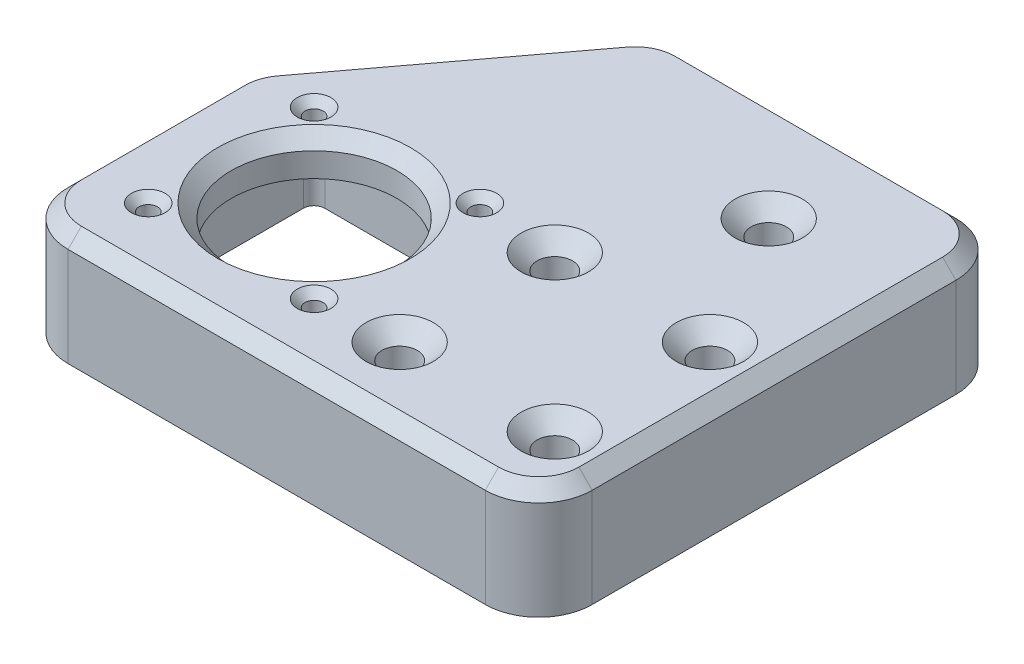
SolidWorks part; units mm, degrees
material "3.1355 (EN-AW 2024)"
ref_plane "Front" through (0, 0, 0) normal (0, 0, 1) x (1, 0, 0)
ref_plane "Top" through (0, 0, 0) normal (0, 1, 0) x (1, 0, 0)
ref_plane "Right" through (0, 0, 0) normal (1, 0, 0) x (0, 0, -1)
sketch "Эскиз1" plane through (0, 0, 0) normal (0, 1, 0) x (1, 0, 0)
  line L1 (-40, 40) -> (40, 40)
  line L2 (-40, 40) -> (-40, -40)
  line L3 (-40, -40) -> (40, -40)
  line L4 (40, 40) -> (40, -40)
  line L5 (-40, 40) -> (40, -40) construction
  line L6 (-40, -40) -> (40, 40) construction
  point P0 (0, 0)
  dimension "D1" = 80
extrude "База" add sketch "Эскиз1" along normal blind 21
sketch "Эскиз9" plane through (0, 21, 0) normal (0, 1, 0) x (1, 0, 0)
  line L6 (40, -40) -> (-40, -40)
  line L7 (-40, -40) -> (-40, 40)
  line L8 (-40, 40) -> (-93, 40)
  line L9 (-93, 40) -> (-93, -48)
  line L10 (-93, -48) -> (40, -48)
  line L11 (40, -48) -> (40, -40)
  dimension "D1" = 8
  dimension "D2" = 53
extrude "База-2" add sketch "Эскиз9" against normal up to surface (21 mm away) up to face at (0, 0, 0)
hole_wizard "Крепление-M6" positions "Эскиз6" profile "Эскиз8" countersink size "M6" standard "DIN" end condition through all
sketch "Эскиз6" plane through (0, 21, 0) normal (0, 1, 0) x (1, 0, 0)
  line L0 (0, 0) -> (-20, 0) construction
  line L1 (-20, 0) -> (-40, 0) construction
  line L5 (0, 0) -> (20, 0) construction
  line L6 (20, 0) -> (40, 0) construction
  line L10 (0, 0) -> (0, -20) construction
  line L11 (0, -20) -> (0, -40) construction
  line L15 (0, 0) -> (0, 20) construction
  line L16 (0, 20) -> (0, 40) construction
  line L20 (-34.5, -34.5) -> (-34.5, -20) construction
  line L21 (-34.5, -20) -> (-34.5, -5.5) construction
  line L26 (-34.5, -34.5) -> (-20, -34.5) construction
  line L27 (-20, -34.5) -> (-5.5, -34.5) construction
  point P0 (20, -20)
  point P2 (-20, 20)
  point P41 (-34.5, -5.5)
  point P43 (-5.5, -5.5)
  point P45 (-5.5, -34.5)
  point P47 (-34.5, -34.5)
  dimension "D1" = 29
  dimension "D2" = 20
sketch "Эскиз8" plane through (20, 21, 20) normal (1, 0, 0) x (0, 0, 1)
  line L0 (0, 0) -> (0, 21)
  line L1 (0, 21) -> (3.3, 21)
  line L2 (3.3, 21) -> (3.3, 3)
  line L3 (3.3, 3) -> (6.3, 0)
  line L5 (6.3, 0) -> (0, 0)
  line L6 (-3.3, 3) -> (-6.3, 0) construction
  line L11 (0, -6.35) -> (0, 107.95) construction
  dimension "Диаметр сквозного отверстия" = 6.6
  dimension "Глубина сквозного отверстия" = 21
  dimension "Диаметр передней зенковки" = 12.6
  dimension "Угол передней зенковки" = 90
sketch "Эскиз10" plane through (0, 0, 0) normal (0, -1, 0) x (1, 0, 0)
  line L1 (-40, 0) -> (0, 0)
  line L2 (-40, 0) -> (-40, 40)
  line L3 (-40, 40) -> (0, 40)
  line L4 (0, 0) -> (0, 40)
  dimension "D1" = 40
extrude "Профиль-40" cut sketch "Эскиз10" against normal blind 11.5
sketch "Эскиз11" plane through (0, 0, 0) normal (0, -1, 0) x (1, 0, 0)
  line L0 (0, 0) -> (0, 40) construction
  line L1 (-86.15, 41.15) -> (-43.85, 41.15)
  line L2 (-86.15, 41.15) -> (-86.15, -1.15)
  line L3 (-86.15, -1.15) -> (-43.85, -1.15)
  line L4 (-43.85, 41.15) -> (-43.85, -1.15)
  line L5 (-86.15, 41.15) -> (-43.85, -1.15) construction
  line L6 (-86.15, -1.15) -> (-43.85, 41.15) construction
  line L7 (-40, 40) -> (-40, 0) construction
  point P0 (-65, 20)
  point P6 (-43.85, 20)
  point P10 (-40, 20)
  point P11 (0, 20)
  dimension "D1" = 42.3
  dimension "D2" = 65
extrude "Nema17" cut sketch "Эскиз11" against normal blind 14
hole_wizard "Nema17-M3" positions "Эскиз12" profile "Эскиз13" countersink size "M3" standard "DIN" end condition through all
sketch "Эскиз12" plane through (0, 21, 0) normal (0, -1, 0) x (-1, 0, 0)
  line L0 (49.5, -4.5) -> (65, -4.5) construction
  line L1 (65, -4.5) -> (80.5, -4.5) construction
  line L2 (80.5, -4.5) -> (80.5, -20) construction
  line L3 (80.5, -20) -> (80.5, -35.5) construction
  line L7 (86.15, 1.15) -> (43.85, 1.15) construction
  line L8 (86.15, -41.15) -> (86.15, 1.15) construction
  point P0 (80.5, -35.5)
  point P2 (49.5, -35.5)
  point P4 (49.5, -4.5)
  point P6 (80.5, -4.5)
  point P28 (65, 1.15)
  point P31 (86.15, -20)
  dimension "D1" = 31
sketch "Эскиз13" plane through (-80.5, 21, 35.5) normal (1, 0, 0) x (0, 0, 1)
  line L0 (0, 0) -> (0, 21)
  line L1 (0, 21) -> (1.7, 21)
  line L2 (1.7, 21) -> (1.7, 1.45)
  line L3 (1.7, 1.45) -> (3.15, 0)
  line L5 (3.15, 0) -> (0, 0)
  line L6 (-1.7, 1.45) -> (-3.15, 0) construction
  line L11 (0, -6.35) -> (0, 107.95) construction
  dimension "Диаметр сквозного отверстия" = 3.4
  dimension "Глубина сквозного отверстия" = 21
  dimension "Диаметр передней зенковки" = 6.3
  dimension "Угол передней зенковки" = 90
fillet "Скругление1" radius 2 8 edges at (-40, 5.75, 40) (0, 5.75, 40) (0, 5.75, 0) (-40, 5.75, 0) (-43.85, 7, -1.15) (-43.85, 7, 41.15) (-86.15, 7, 41.15) (-86.15, 7, -1.15)
sketch "Эскиз14" plane through (0, 14, 0) normal (0, -1, 0) x (1, 0, 0)
  line L0 (-86.15, 39.15) -> (-86.15, 0.85) construction
  line L1 (-45.85, 41.15) -> (-84.15, 41.15) construction
  circle A0 centre (-65, 20) radius 15.5
  point P4 (-86.15, 20)
  point P7 (-65, 41.15)
  dimension "D1" = 31
extrude "Вырез-Nema23" cut sketch "Эскиз14" against normal through all
sketch "Эскиз2" plane through (0, 21, 0) normal (0, 1, 0) x (1, 0, 0)
  line L6 (40, 40) -> (-93, 40) construction
  line L8 (40, -48) -> (5, -48)
  line L13 (40, -48) -> (40, 40)
  line L14 (40, 40) -> (5, 40)
  line L15 (5, -48) -> (5, 40)
  line L16 (0, -2) -> (0, -38) construction
  dimension "D1" = 5
extrude "Срез" cut sketch "Эскиз2" against normal through all
sketch "Эскиз15" plane through (0, 21, 0) normal (0, 1, 0) x (1, 0, 0)
  line L0 (-93, -4) -> (-60, 40)
  line L1 (-93, 40) -> (-93, -48) construction
  line L3 (-60, 40) -> (-93, 40)
  line L4 (-93, 40) -> (-93, -4)
  dimension "D1" = 60
extrude "Вырез-Вытянуть1" cut sketch "Эскиз15" against normal through all
fillet "Скругление2" radius 10 5 edges at (5, 10.5, -40) (5, 10.5, 48) (-93, 10.5, 48) (-93, 10.5, 4) (-60, 10.5, -40)
chamfer "Фаска1" distance 2.5 angle 45 11 edges at (-44, 21, 48) (2.0711, 21, 45.0711) (5, 21, 4) (2.0711, 21, -37.0711) (-30, 21, -40) (-93, 21, 22.6667) (-90.0711, 21, 45.0711) (-65, 21, 4.5) (-77, 21, -17.3333) (-59.4721, 21, -38.9443) (-92.4868, 21, 4.1711)
